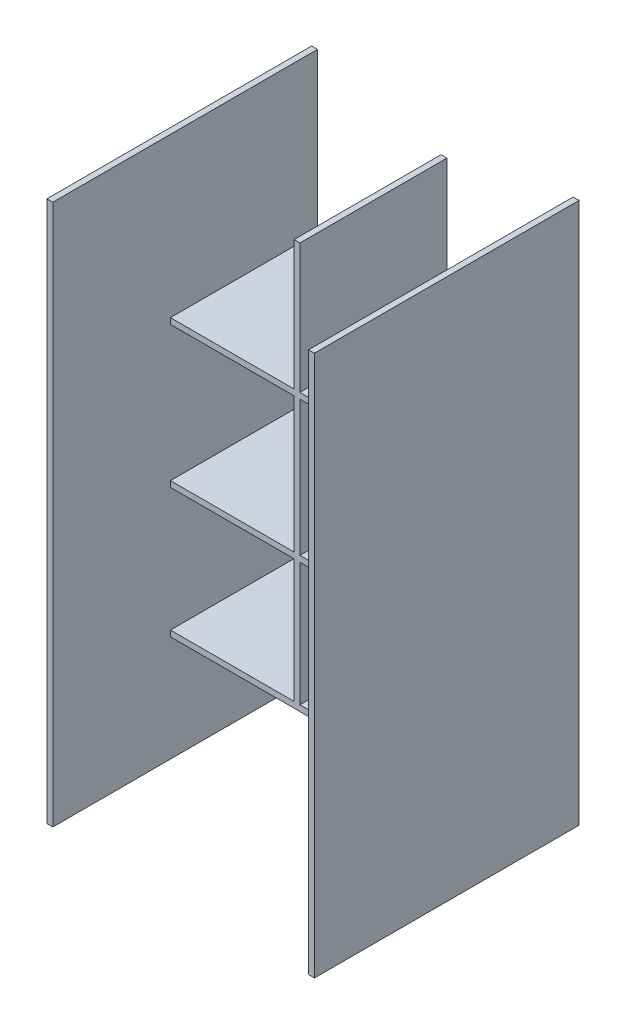
SolidWorks part; units mm, degrees
ref_plane "Alzado" through (0, 0, 0) normal (0, 0, 1) x (1, 0, 0)
ref_plane "Planta" through (0, 0, 0) normal (0, 1, 0) x (1, 0, 0)
ref_plane "Vista lateral" through (0, 0, 0) normal (1, 0, 0) x (0, 0, -1)
sketch "Croquis1" plane through (0, 0, 0) normal (0, 0, 1) x (1, 0, 0)
  line L1 (250, -345) -> (-250, -345)
  line L2 (250, -345) -> (250, 345)
  line L3 (250, 345) -> (-250, 345)
  line L4 (-250, -345) -> (-250, 345)
  line L5 (250, -345) -> (-250, 345) construction
  line L6 (250, 345) -> (-250, -345) construction
  point P0 (0, 0)
  dimension "D1" = 500
  dimension "D2" = 690
extrude "Saliente-Extruir1" add sketch "Croquis1" against normal blind 350
sketch "Croquis2" plane through (0, 0, 0) normal (0, 0, 1) x (1, 0, 0)
  line L0 (250, 345) -> (-250, 345) construction
  line L1 (5, -345) -> (-5, -345)
  line L2 (5, -335) -> (5, -125)
  line L3 (5, 345) -> (-5, 345)
  line L4 (-5, -335) -> (-5, -125)
  line L5 (5, -335) -> (250, -335)
  line L6 (-5, -115) -> (-5, 115)
  line L7 (-250, 345) -> (-250, -345) construction
  line L8 (-250, 115) -> (-5, 115)
  line L9 (-250, 115) -> (-250, 125)
  line L10 (-250, 125) -> (-5, 125)
  line L11 (250, 115) -> (250, 125)
  line L12 (250, -345) -> (250, 345) construction
  line L13 (-5, 125) -> (-5, 345)
  line L14 (-250, -115) -> (-5, -115)
  line L15 (-250, -115) -> (-250, -125)
  line L16 (-250, -125) -> (-5, -125)
  line L17 (250, -115) -> (250, -125)
  line L18 (5, -115) -> (250, -115)
  line L19 (-250, 345) -> (250, 345)
  line L20 (5, 125) -> (5, 345)
  line L21 (5, 125) -> (250, 125)
  line L22 (5, 115) -> (250, 115)
  line L23 (-250, -335) -> (-5, -335)
  line L24 (-250, -335) -> (-250, -345)
  line L25 (5, -115) -> (5, 115)
  line L26 (5, -125) -> (250, -125)
  line L27 (-250, 345) -> (-250, -345)
  line L28 (-250, -345) -> (250, -345)
  line L29 (250, 345) -> (250, -345)
  line L30 (-250, -345) -> (250, -345)
  line L31 (250, -335) -> (250, -345)
  point P0 (0, 0)
  dimension "D1" = 230
  dimension "D2" = 10
  dimension "D3" = 10
  dimension "D4" = 230
  dimension "D5" = 10
  dimension "D6" = 690
  dimension "D7" = 5
  dimension "D8" = 10
extrude "Cortar-Extruir5" cut sketch "Croquis2" against normal through all contours L10 L13 L22 | L20 L21 L22 | L13 L14 L6 L8 | L25 L18 L21 L22 | L13 L23 L4 L16 | L26 L2 L5 L21
sketch "Croquis6" plane through (0, 0, -350) normal (0, 0, -1) x (-1, 0, 0)
  line L0 (0, 345) -> (0, 330) construction
  line L1 (-5, 345) -> (5, 345) construction
  line L2 (0, 0) -> (-10.2174, 0) construction
  circle A0 centre (0, 330) radius 2.5
  circle A1 centre (0, -330) radius 2.5
  dimension "D2" = 5
  dimension "D1" = 15
  dimension "D3" = 660
extrude "Cortar-Extruir6" cut sketch "Croquis6" against normal blind 10
sketch "Croquis7" plane through (0, 0, -350) normal (0, 0, -1) x (-1, 0, 0)
  line L0 (-5, -335) -> (0, -335) construction
  line L1 (0, -335) -> (0, -320) construction
  dimension "D1" = 15
sketch "Croquis8" plane through (0, 0, 0) normal (0, 0, 1) x (1, 0, 0)
  line L1 (-225.0888, 361.6032) -> (229.6545, 361.6032)
  line L2 (-225.0888, 361.6032) -> (-225.0888, -366.1689)
  line L3 (-225.0888, -366.1689) -> (229.6545, -366.1689)
  line L4 (229.6545, 361.6032) -> (229.6545, -366.1689)
extrude "Cortar-Extruir7" cut sketch "Croquis8" against normal blind 100
sketch "Croquis10" plane through (0, 0, -100) normal (0, 0, 1) x (1, 0, 0)
  line L1 (-225.0888, 125) -> (-215.0888, 125)
  line L2 (-225.0888, 125) -> (-225.0888, 345)
  line L3 (-225.0888, 345) -> (-215.0888, 345)
  line L4 (-215.0888, 125) -> (-215.0888, 345)
  line L8 (0, 345) -> (0, -378.7907) construction
  line L9 (-5, 345) -> (5, 345) construction
  line L10 (219.6545, 115) -> (219.6545, 345.2438)
  line L11 (229.6545, 345.0454) -> (219.6545, 345.2438)
  line L12 (229.6545, 125) -> (229.6545, 345.0454)
  line L14 (0, 0) -> (267.7459, 0) construction
  line L16 (-225.0888, -115) -> (-215.0888, -115)
  line L17 (-225.0888, -115) -> (-225.0888, 115)
  line L18 (-225.0888, 115) -> (-215.0888, 115)
  line L19 (-215.0888, -115) -> (-215.0888, 115)
  line L20 (229.6545, -115) -> (219.6545, -115)
  line L21 (229.6545, -115) -> (229.6545, 115)
  line L23 (219.6545, -115) -> (219.6545, 115)
  line L24 (-225.0888, -335) -> (-215.0888, -335)
  line L25 (-225.0888, -335) -> (-225.0888, -115)
  line L26 (-225.0888, -115) -> (-215.0888, -115)
  line L27 (-215.0888, -335) -> (-215.0888, -115)
  line L28 (229.6545, -335) -> (219.6545, -335)
  line L29 (229.6545, -335) -> (229.6545, -115)
  line L30 (229.6545, -115) -> (219.6545, -115)
  line L31 (219.6545, -335) -> (219.6545, -115)
  point P22 (219.6545, 0)
  line M20 (229.6545, -335) -> (5, -335)
  line M22 (5, -125) -> (229.6545, -125)
  line M24 (229.6545, -115) -> (5, -115)
  line M26 (5, 115) -> (229.6545, 115)
  line M28 (229.6545, 125) -> (5, 125)
  line M38 (-225.0888, -125) -> (-5, -125)
  line M40 (-5, -335) -> (-225.0888, -335)
  dimension "D1" = 10
  dimension "D2" = 220
  dimension "D3" = 230
  dimension "D4" = 230
  dimension "D5" = 10
  dimension "D6" = 10
  dimension "D7" = 10
  dimension "D8" = 220
  dimension "D9" = 220
  dimension "D10" = 10
  dimension "D11" = 220.0454
  dimension "D12" = 10
  dimension "D13" = 219.6545
extrude "Saliente-Extruir2" add sketch "Croquis10" against normal up to surface (250 mm away) contours L12 L11 L10 M28 | L23 L21 M24 M26 | L31 L29 M20 M22 | L27 L25 M40 M38 | L19 L18 L17 L16 | L2 L3 L4 L1 up to face at (-2.5, 330, -350)
sketch "Croquis11" plane through (0, 125, 0) normal (0, 1, 0) x (1, 0, 0)
  line L0 (219.6545, 100) -> (5, 100) construction
  line L1 (-285.0553, 100) -> (279.4309, 100)
  line L2 (-285.0553, 100) -> (-285.0553, -31.0721)
  line L3 (-285.0553, -31.0721) -> (279.4309, -31.0721)
  line L4 (279.4309, 100) -> (279.4309, -31.0721)
extrude "Cortar-Extruir8" cut sketch "Croquis11" against normal through all
sketch "Croquis12" plane through (0, 125, 0) normal (0, 1, 0) x (1, 0, 0)
  line L1 (250, 350) -> (229.6545, 350)
  line L2 (250, 350) -> (250, 100)
  line L3 (250, 100) -> (229.6545, 100)
  line L4 (229.6545, 350) -> (229.6545, 100)
  line L5 (-250, 350) -> (-225.0888, 350)
  line L6 (-250, 350) -> (-250, 100)
  line L7 (-250, 100) -> (-225.0888, 100)
  line L8 (-225.0888, 350) -> (-225.0888, 100)
extrude "Cortar-Extruir9" cut sketch "Croquis12" against normal through all
sketch "Croquis13" plane through (0, 0, -100) normal (0, 0, 1) x (1, 0, 0)
  line L0 (219.6545, -335) -> (219.6545, -125) construction
  line L1 (229.6545, 395) -> (219.6545, 395)
  line L2 (229.6545, 395) -> (229.6545, -525)
  line L3 (229.6545, -525) -> (219.6545, -525)
  line L4 (219.6545, 395) -> (219.6545, -525)
  line L5 (229.6545, -345) -> (-225.0888, -345) construction
  line L7 (-215.0888, 395) -> (-215.0888, -525)
  line L8 (-225.0888, -525) -> (-215.0888, -525)
  line L9 (-225.0888, 395) -> (-225.0888, -525)
  line L10 (-225.0888, 395) -> (-215.0888, 395)
  line L11 (-225.0888, -345) -> (-225.0888, 345) construction
  point P8 (224.6545, -525)
  dimension "D1" = 10
  dimension "D2" = 180
  dimension "D3" = 920
extrude "Saliente-Extruir3" add sketch "Croquis13" against normal up to surface (250 mm away) up to face at (-110.0444, -230, -350)
sketch "Croquis15" plane through (0, 0, -100) normal (0, 0, 1) x (1, 0, 0)
  line L0 (0, 0) -> (0, 395) construction
  line L1 (219.6545, 395) -> (229.6545, 395)
  line L2 (219.6545, 395) -> (219.6545, -525)
  line L3 (219.6545, -525) -> (229.6545, -525)
  line L4 (229.6545, 395) -> (229.6545, -525)
  line L6 (-225.0888, 395) -> (-215.0888, 395)
  line L7 (-225.0888, 395) -> (-225.0888, -525)
  line L8 (-225.0888, -525) -> (-215.0888, -525)
  line L9 (-215.0888, 395) -> (-215.0888, -525)
  dimension "D1" = 920
extrude "Saliente-Extruir4" add sketch "Croquis15" along normal blind 200
